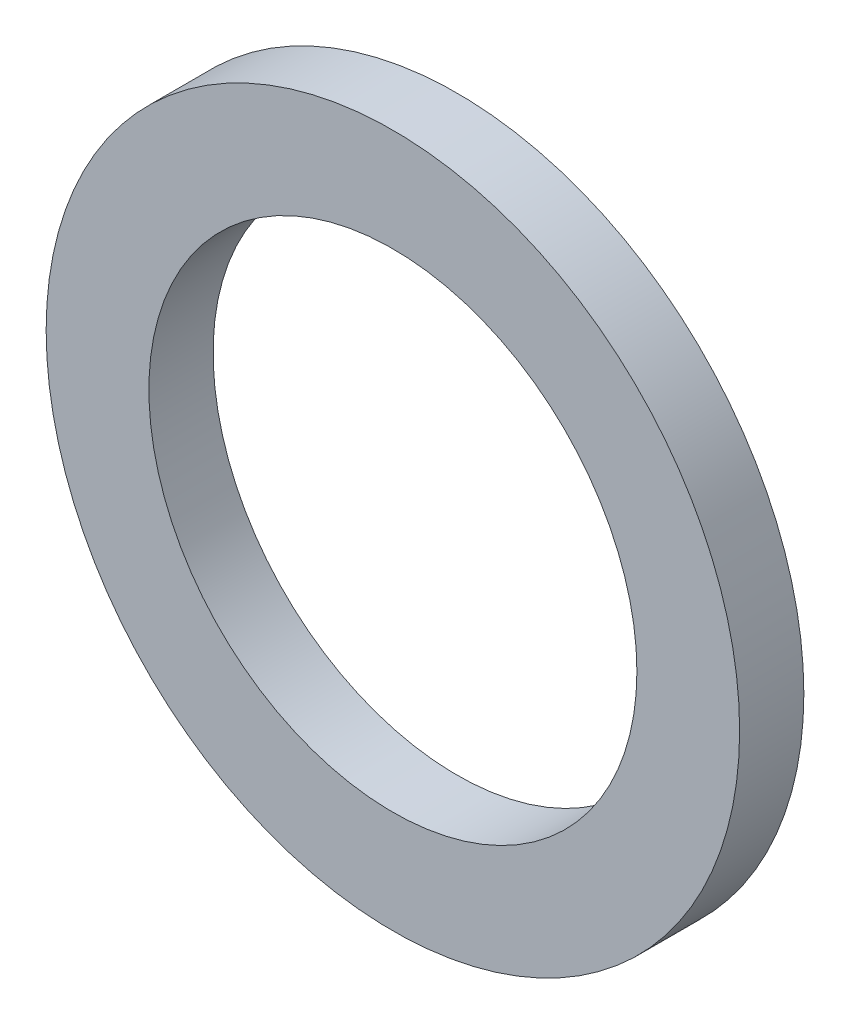
SolidWorks part; units mm, degrees
material "1.0037 (S235JR)"
ref_plane "Front Plane" through (0, 0, 0) normal (0, 0, 1) x (1, 0, 0)
ref_plane "Top Plane" through (0, 0, 0) normal (0, 1, 0) x (1, 0, 0)
ref_plane "Right Plane" through (0, 0, 0) normal (1, 0, 0) x (0, 0, -1)
sketch "Sketch1" plane through (0, 0, 0) normal (0, 0, 1) x (1, 0, 0)
  circle A0 centre (0, 0) radius 27
  circle A1 centre (0, 0) radius 19
  dimension "D1" = 38
  dimension "D2" = 54
extrude "Boss-Extrude1" add sketch "Sketch1" along normal blind 5
